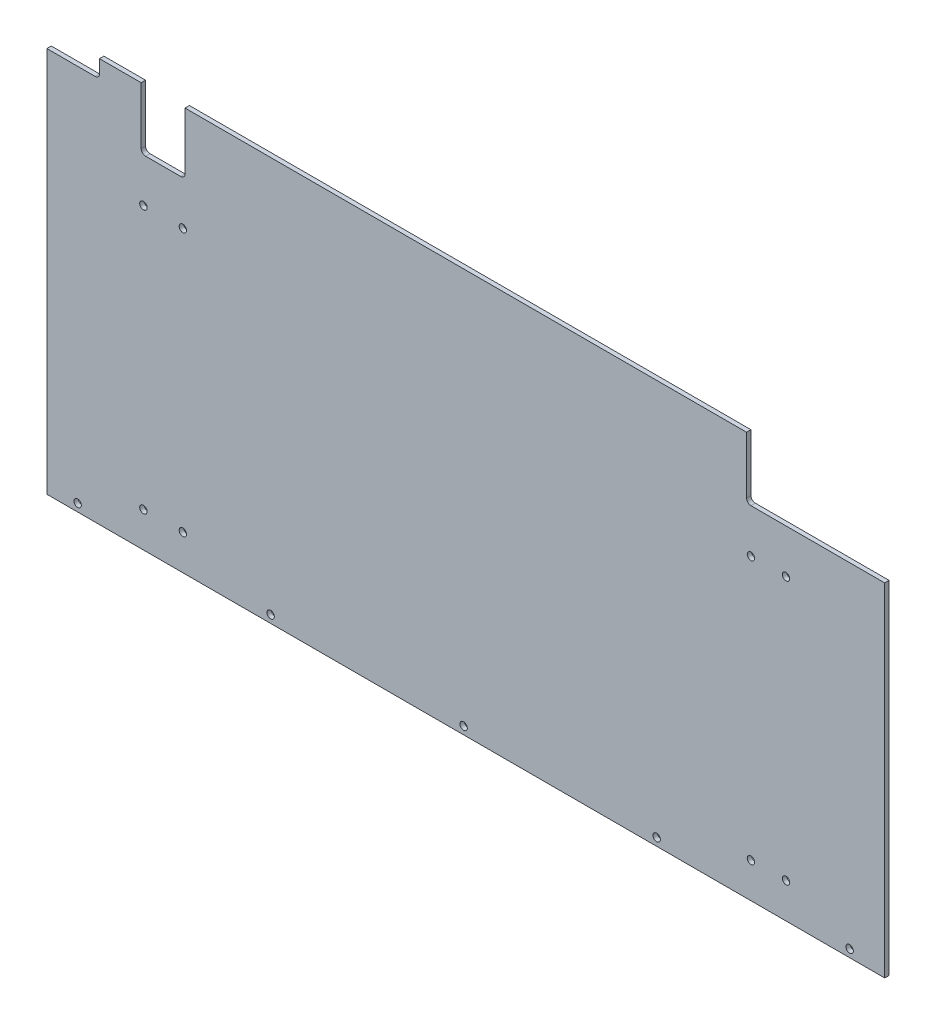
SolidWorks part; units mm, degrees
material "PC High Viscosity"
ref_plane "Front Plane" through (0, 0, 0) normal (0, 0, 1) x (1, 0, 0)
ref_plane "Top Plane" through (0, 0, 0) normal (0, 1, 0) x (1, 0, 0)
ref_plane "Right Plane" through (0, 0, 0) normal (1, 0, 0) x (0, 0, -1)
sketch "Sketch1" plane through (0, 0, 0) normal (0, 0, 1) x (1, 0, 0)
  line L1 (-606.425, 292.1) -> (606.425, 292.1)
  line L2 (-606.425, 292.1) -> (-606.425, -292.1)
  line L3 (-606.425, -292.1) -> (606.425, -292.1)
  line L4 (606.425, 292.1) -> (606.425, -292.1)
  line L5 (-606.425, 292.1) -> (606.425, -292.1) construction
  line L6 (-606.425, -292.1) -> (606.425, 292.1) construction
  point P0 (0, 0)
  dimension "D1" = 1212.85
  dimension "D2" = 584.2
extrude "Boss-Extrude1" add sketch "Sketch1" along normal mid plane 6.35
sketch "Sketch2" plane through (0, 0, 3.175) normal (0, 0, 1) x (1, 0, 0)
  line L0 (606.425, 292.1) -> (-606.425, 292.1) construction
  line L1 (469.9, 292.1) -> (406.4, 292.1)
  line L2 (469.9, 292.1) -> (469.9, 203.2)
  line L3 (469.9, 203.2) -> (406.4, 203.2)
  line L4 (406.4, 292.1) -> (406.4, 203.2)
  line L5 (438.15, 203.2) -> (438.15, 292.1) construction
  line L6 (469.9, 247.65) -> (406.4, 247.65) construction
  line L8 (0, -292.1) -> (0, 292.1) construction
  line L9 (-606.425, -292.1) -> (606.425, -292.1) construction
  line L18 (-469.9, 247.65) -> (-406.4, 247.65) construction
  line L19 (-438.15, 203.2) -> (-438.15, 292.1) construction
  line L24 (-406.4, 292.1) -> (-406.4, 203.2)
  line L25 (-469.9, 203.2) -> (-406.4, 203.2)
  line L26 (-469.9, 292.1) -> (-469.9, 203.2)
  line L27 (-469.9, 292.1) -> (-406.4, 292.1)
  circle A0 centre (-466.725, 139.7) radius 5.3578
  circle A1 centre (-409.575, 139.7) radius 5.3578
  circle A2 centre (-466.725, -241.3) radius 5.3578
  circle A3 centre (-409.575, -241.3) radius 5.3578
  circle A4 centre (412.75, 139.7) radius 5.3578
  circle A5 centre (463.55, 139.7) radius 5.3578
  circle A6 centre (412.75, -241.3) radius 5.3578
  circle A7 centre (463.55, -241.3) radius 5.3578
  point P32 (-438.15, 247.65)
  point P384 (438.15, 247.65)
  dimension "D4" = 10.7156
  dimension "D6" = 28.575
  dimension "D1" = 438.15
  dimension "D2" = 63.5
  dimension "D3" = 88.9
  dimension "D5" = 28.575
  dimension "D7" = 25.4
  dimension "D8" = 25.4
  dimension "D9" = 431.8
  dimension "D10" = 50.8
extrude "Cut-Extrude1" cut sketch "Sketch2" against normal through all
fillet "Fillet1" radius 6.35 4 edges at (469.9, 203.2, 0) (406.4, 203.2, 0) (-406.4, 203.2, 0) (-469.9, 203.2, 0)
sketch "Sketch3" plane through (0, 0, 3.175) normal (0, 0, 1) x (1, 0, 0)
  line L0 (463.55, 203.2) -> (606.425, 203.2)
  line L1 (606.425, -292.1) -> (606.425, 292.1) construction
  line L2 (606.425, 203.2) -> (606.425, 292.1)
  line L3 (606.425, 292.1) -> (463.55, 292.1)
  line L4 (463.55, 292.1) -> (463.55, 203.2)
  line L5 (606.425, 292.1) -> (469.9, 292.1) construction
extrude "Cut-Extrude2" cut sketch "Sketch3" against normal through all
hole_wizard "27/64 (0.42188) Diameter Hole1" positions "Sketch4" profile "Sketch5" hole size "27/64" standard "ANSI Inch" end condition up to next
sketch "Sketch4" plane through (0, 0, 3.175) normal (0, 0, 1) x (1, 0, 0)
  line L0 (-606.425, 292.1) -> (-606.425, -292.1) construction
  line L1 (-606.425, -292.1) -> (606.425, -292.1) construction
  point P0 (-561.975, -280.9875)
  dimension "D1" = 44.45
  dimension "D2" = 11.1125
sketch "Sketch5" plane through (-561.975, -280.9875, 3.175) normal (1, 0, 0) x (0, -1, 0)
  line L0 (0, 0) -> (0, 6.35)
  line L1 (0, 6.35) -> (5.3579, 6.35)
  line L2 (5.3579, 6.35) -> (5.3579, 0)
  line L5 (5.3579, 0) -> (0, 0)
  line L11 (0, -6.35) -> (0, 107.95) construction
  dimension "Thru Hole Dia." = 10.7158
  dimension "Thru Hole Depth" = 6.35
pattern_linear "LPattern1" count 5 spacing 279.4 along (1, 0, 0) of "27/64 (0.42188) Diameter Hole1"
sketch "Sketch6" plane through (0, 0, 3.175) normal (0, 0, 1) x (1, 0, 0)
  line L0 (-606.425, 292.1) -> (-606.425, -292.1) construction
  line L3 (-606.425, 266.7) -> (-536.575, 266.7)
  line L4 (-530.225, 292.1) -> (-530.225, 273.05)
  line L5 (-469.9, 292.1) -> (-606.425, 292.1) construction
  line L6 (-606.425, 292.1) -> (-606.425, -292.1)
  line L7 (-469.9, 292.1) -> (-606.425, 292.1)
  arc A0 (-536.575, 266.7) -> (-530.225, 273.05) centre (-536.575, 273.05) ccw
  point P4 (-577.6668, 264.985)
  point P12 (-530.225, 266.7)
  line M17 (-469.9, 292.1) -> (-606.425, 292.1)
  line M18 (-606.425, 292.1) -> (-606.425, -292.1)
  dimension "D3" = 6.35
  dimension "D1" = 76.2
  dimension "D2" = 25.4
extrude "Cut-Extrude3" cut sketch "Sketch6" against normal through all contours L3 A0 L4 M17 M18
